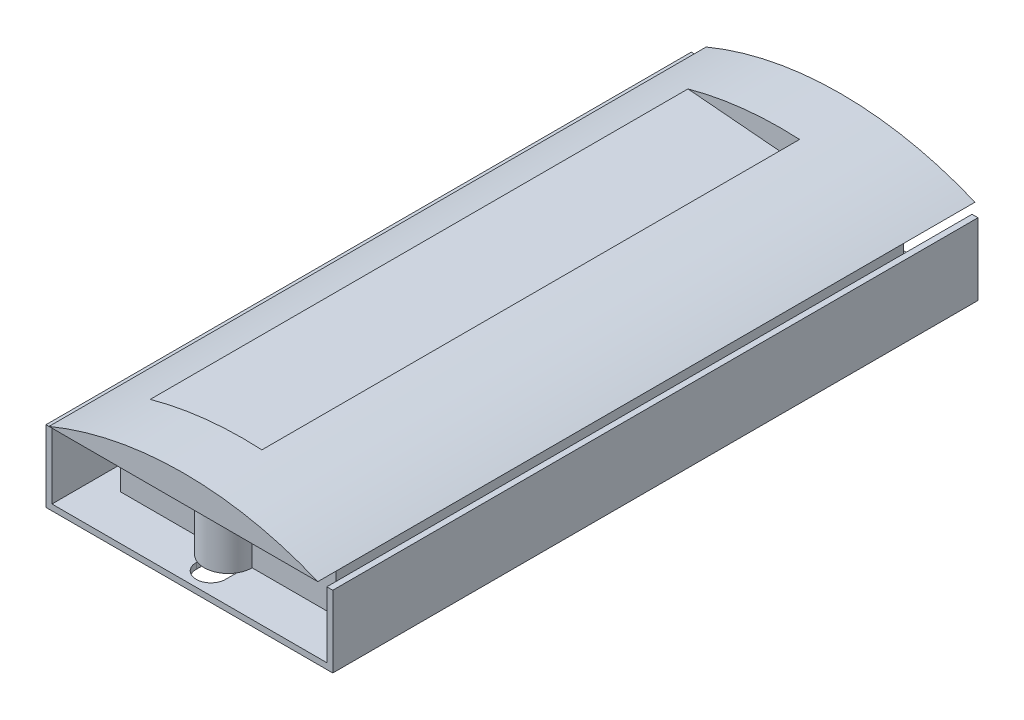
SolidWorks part; units mm, degrees
ref_plane "前视基准面" through (0, 0, 0) normal (0, 0, 1) x (1, 0, 0)
ref_plane "上视基准面" through (0, 0, 0) normal (0, 1, 0) x (1, 0, 0)
ref_plane "右视基准面" through (0, 0, 0) normal (1, 0, 0) x (0, 0, -1)
sketch "草图1" plane through (0, 0, 0) normal (0, 0, 1) x (1, 0, 0)
  line L0 (0, 0) -> (45, 0)
  arc A0 (0, 0) -> (45, 0) centre (22.5, -54) cw
  point P3 (22.5, 4.5)
  dimension "D1" = 45
  dimension "D2" = 4.5
extrude "凸台-拉伸1" add sketch "草图1" along normal blind 110
sketch "草图2" plane through (0, 0, 0) normal (0, -1, 0) x (-1, 0, 0)
  line L0 (0, -55) -> (-45, -55) construction
  line L1 (0, -110) -> (0, 0) construction
  line L2 (-45, -110) -> (-45, 0) construction
  line L3 (-22.5, -7.5) -> (-22.5, -102.5) construction
  line L4 (-4.5, -7.5) -> (-40.5, -7.5)
  line L5 (-4.5, -7.5) -> (-4.5, -102.5)
  line L6 (-4.5, -102.5) -> (-40.5, -102.5)
  line L7 (-40.5, -7.5) -> (-40.5, -102.5)
  line L8 (-4.5, -7.5) -> (-40.5, -102.5) construction
  line L9 (-4.5, -102.5) -> (-40.5, -7.5) construction
  line L10 (-18.5, -7.5) -> (-18.5, -102.5)
  line L11 (-26.5, -7.5) -> (-26.5, -102.5)
  arc A0 (-18.5, -7.5) -> (-26.5, -7.5) centre (-22.5, -7.5) ccw
  arc A1 (-26.5, -102.5) -> (-18.5, -102.5) centre (-22.5, -102.5) ccw
  point P6 (-22.5, -55)
  point P13 (-22.5, -55)
  point P18 (-22.5, -106.5)
  point P19 (-22.5, -3.5)
  dimension "D1" = 36
  dimension "D2" = 95
  dimension "D3" = 8
  dimension "D4" = 103
extrude "凸台-拉伸2" add sketch "草图2" along normal blind 11 contours L4 L10 L6 L5 | L4 L11 L6 L10 | L6 A1 | L11 L4 L7 L6 | L4 A0
sketch "草图3" plane through (0, -11, 0) normal (0, -1, 0) x (1, 0, 0)
  circle A0 centre (22.5, 102.5) radius 1.6
  circle A1 centre (22.5, 7.5) radius 1.6
  dimension "D1" = 3.2
extrude "切除-拉伸1" cut sketch "草图3" against normal blind 11
ref_plane "基准面1" through (0, -12, 0) normal (0, -1, 0) x (-1, 0, 0)
sketch "草图4" plane through (0, -12, 0) normal (0, -1, 0) x (-1, 0, 0)
  line L0 (-40.5, -55) -> (-4.5, -55) construction
  line L1 (-40.5, -7.5) -> (-40.5, -102.5) construction
  line L2 (-4.5, -7.5) -> (-4.5, -102.5) construction
  line L3 (-22.5, -4.6) -> (-22.5, -10.4) construction
  line L4 (-46.5, -109) -> (1.5, -109)
  line L5 (-46.5, -109) -> (-46.5, -1)
  line L6 (-46.5, -1) -> (1.5, -1)
  line L7 (1.5, -109) -> (1.5, -1)
  line L8 (-46.5, -109) -> (1.5, -1) construction
  line L9 (-46.5, -1) -> (1.5, -109) construction
  line L10 (-20.05, -4.6) -> (-20.05, -10.4)
  line L11 (-24.95, -4.6) -> (-24.95, -10.4)
  line L12 (-22.5, -105.4) -> (-22.5, -99.6) construction
  line L13 (-20.05, -105.4) -> (-20.05, -99.6)
  line L14 (-24.95, -105.4) -> (-24.95, -99.6)
  arc A0 (-20.05, -4.6) -> (-24.95, -4.6) centre (-22.5, -4.6) ccw
  arc A1 (-24.95, -10.4) -> (-20.05, -10.4) centre (-22.5, -10.4) ccw
  arc A2 (-20.05, -105.4) -> (-24.95, -105.4) centre (-22.5, -105.4) cw
  arc A3 (-24.95, -99.6) -> (-20.05, -99.6) centre (-22.5, -99.6) cw
  point P6 (-22.5, -55)
  point P13 (-22.5, -7.5)
  point P21 (-22.5, -102.5)
  dimension "D1" = 48
  dimension "D2" = 108
  dimension "D3" = 4.9
  dimension "D4" = 5.8
extrude "凸台-拉伸3" add sketch "草图4" along normal blind 1 separate body
sketch "草图5" plane through (0, 0, 109) normal (0, 0, 1) x (1, 0, 0)
  line L0 (22.5, -13) -> (22.5, -16.1921) construction
  line L1 (-1.5, -13) -> (-0.5, -13)
  line L2 (-1.5, -13) -> (-1.5, -1)
  line L3 (-1.5, -1) -> (-0.5, -1)
  line L4 (-0.5, -13) -> (-0.5, -1)
  line L5 (46.5, -13) -> (-1.5, -13) construction
  line L6 (45.5, -13) -> (45.5, -1)
  line L7 (46.5, -1) -> (45.5, -1)
  line L8 (46.5, -13) -> (46.5, -1)
  line L9 (46.5, -13) -> (45.5, -13)
  dimension "D1" = 1
  dimension "D2" = 12
extrude "凸台-拉伸4" add sketch "草图5" against normal up to surface (108 mm away) up to face at (22.5, -12.5, 1)
ref_plane "基准面2" through (0, 0, 55) normal (0, 0, -1) x (-1, 0, 0)
sketch "草图6" plane through (0, 0, 55) normal (0, 0, -1) x (-1, 0, 0)
  line L0 (-25.6355, 4.4159) -> (-28.8797, 3.1149)
  line L3 (-21.709, 7.7542) -> (-25.6355, 4.4159)
  line L4 (-28.8797, 0.4972) -> (-5.3884, 2.5313)
  line L5 (-21.709, 7.7542) -> (-5.3884, 2.5313)
  arc A0 (0, 0) -> (-45, 0) centre (-22.5, -54) ccw construction
  arc A1 (-28.8797, 0.4972) -> (-28.8797, 3.1149) centre (-28.3548, 1.8061) cw
extrude "切除-拉伸2" cut sketch "草图6" against normal blind 45 and the other way blind 45
